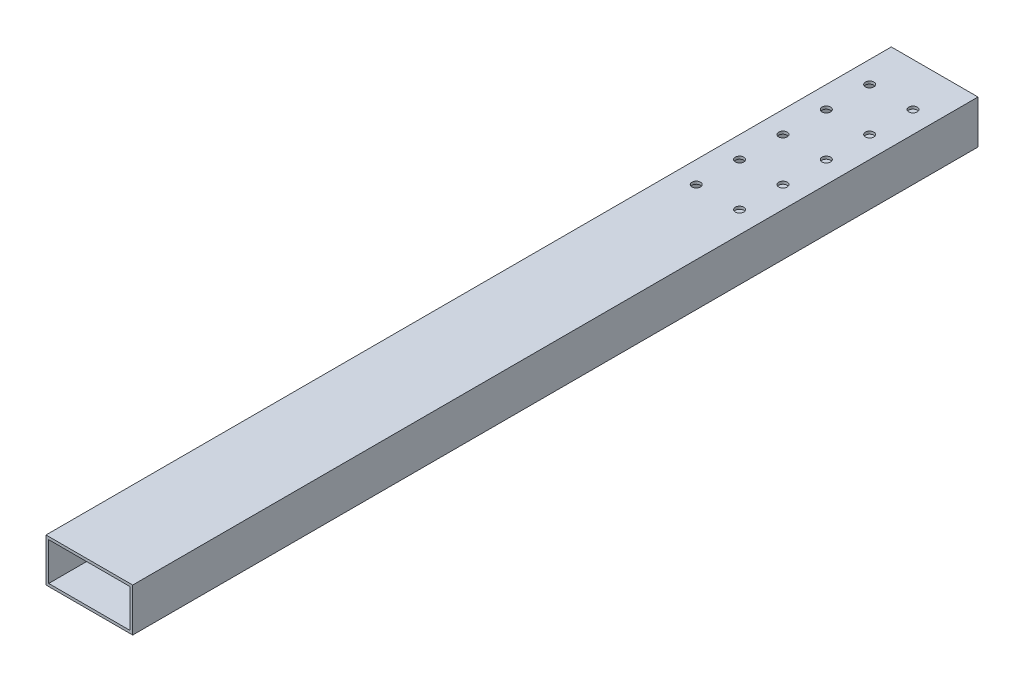
SolidWorks part; units mm, degrees
material "6061-T6 (SS)"
ref_plane "Front Plane" through (0, 0, 0) normal (0, 0, 1) x (1, 0, 0)
ref_plane "Top Plane" through (0, 0, 0) normal (0, 1, 0) x (1, 0, 0)
ref_plane "Right Plane" through (0, 0, 0) normal (1, 0, 0) x (0, 0, -1)
sketch "Sketch1" plane through (0, 0, 0) normal (0, 0, 1) x (1, 0, 0)
  line L1 (-25.4, -12.7) -> (25.4, -12.7)
  line L2 (-25.4, -12.7) -> (-25.4, 12.7)
  line L3 (-25.4, 12.7) -> (25.4, 12.7)
  line L4 (25.4, -12.7) -> (25.4, 12.7)
  line L5 (-25.4, -12.7) -> (25.4, 12.7) construction
  line L6 (-25.4, 12.7) -> (25.4, -12.7) construction
  point P0 (0, 0)
  dimension "D1" = 50.8
  dimension "D2" = 25.4
extrude "Boss-Extrude1" add sketch "Sketch1" along normal blind 495.3 contours L3 L4 L1 L2
shell "Shell1" thickness 1.5875
sketch "Sketch2" plane through (0, 12.7, 0) normal (0, 1, 0) x (1, 0, 0)
  line L0 (-25.4, 0) -> (25.4, 0) construction
  circle A0 centre (-12.7, -25.4) radius 2.4892
  circle A1 centre (12.7, -25.4) radius 2.4892
  circle A2 centre (12.7, -50.8) radius 2.4892
  circle A3 centre (12.7, -76.2) radius 2.4892
  circle A4 centre (12.7, -101.6) radius 2.4892
  circle A5 centre (12.7, -127) radius 2.4892
  circle A6 centre (-12.7, -50.8) radius 2.4892
  circle A7 centre (-12.7, -76.2) radius 2.4892
  circle A8 centre (-12.7, -101.6) radius 2.4892
  circle A9 centre (-12.7, -127) radius 2.4892
  point P23 (0, 0)
  dimension "D5" = 4.9784
  dimension "D6" = 12.7
  dimension "D3" = 25.4
  dimension "D4" = 25.4
  dimension "D7" = 25.4
  dimension "D1" = 2
  dimension "D2" = 5
extrude "Cut-Extrude1" cut sketch "Sketch2" against normal up to next
